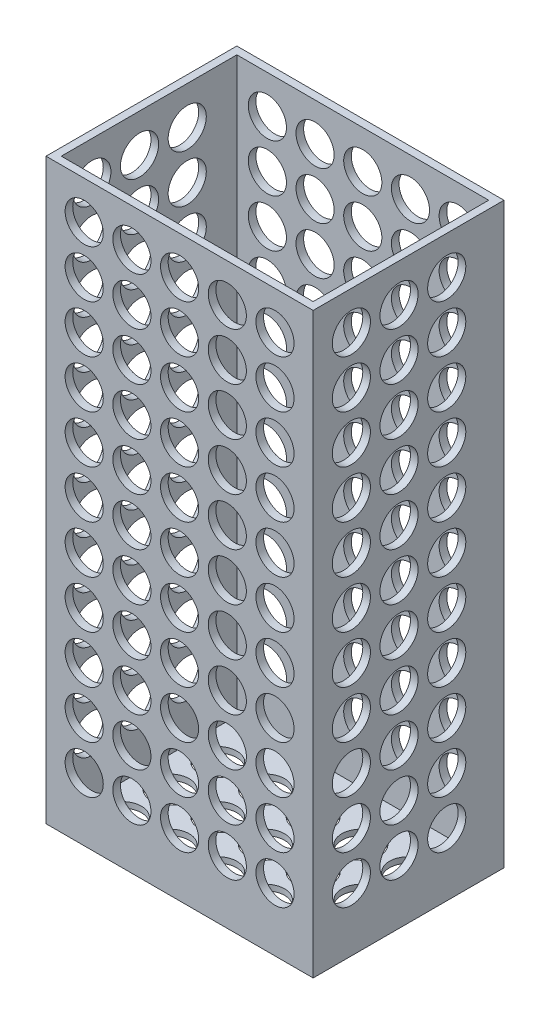
SolidWorks part; units mm, degrees
ref_plane "Front Plane" through (0, 0, 0) normal (0, 0, 1) x (1, 0, 0)
ref_plane "Top Plane" through (0, 0, 0) normal (0, 1, 0) x (1, 0, 0)
ref_plane "Right Plane" through (0, 0, 0) normal (1, 0, 0) x (0, 0, -1)
sketch "Sketch1" plane through (0, 0, 0) normal (0, 1, 0) x (1, 0, 0)
  line L1 (-35, -25) -> (35, -25)
  line L2 (-35, -25) -> (-35, 25)
  line L3 (-35, 25) -> (35, 25)
  line L4 (35, -25) -> (35, 25)
  line L5 (-35, -25) -> (35, 25) construction
  line L6 (-35, 25) -> (35, -25) construction
  point P0 (0, 0)
  dimension "D1" = 50
  dimension "D2" = 70
extrude "Boss-Extrude1" add sketch "Sketch1" along normal blind 1.5
sketch "Sketch2" plane through (0, 1.5, 0) normal (0, 1, 0) x (1, 0, 0)
  line L0 (-33, 23) -> (-33, -23)
  line L1 (-33, -23) -> (33, -23)
  line L2 (33, -23) -> (33, 23)
  line L3 (33, 23) -> (-33, 23)
  line L4 (35, -25) -> (35, 25)
  line L5 (35, 25) -> (-35, 25)
  line L6 (-35, 25) -> (-35, -25)
  line L7 (-35, -25) -> (35, -25)
  line L8 (35, -25) -> (35, 25)
  line L9 (35, 25) -> (-35, 25)
  line L10 (-35, 25) -> (-35, -25)
  line L11 (-35, -25) -> (35, -25)
  dimension "D1" = 0
  dimension "D2" = 2
extrude "Boss-Extrude2" add sketch "Sketch2" along normal blind 150
sketch "Sketch4" plane through (0, 0, 25) normal (0, 0, 1) x (1, 0, 0)
  line L0 (-35, 151.5) -> (35, 151.5) construction
  line L1 (-35, 151.5) -> (-35, 0) construction
  circle A0 centre (-25, 141.5) radius 5
  circle A1 centre (-12.5, 141.5) radius 5
  circle A2 centre (0, 141.5) radius 5
  circle A3 centre (12.5, 141.5) radius 5
  circle A4 centre (25, 141.5) radius 5
  circle A5 centre (-12.5, 129) radius 5
  circle A6 centre (0, 129) radius 5
  circle A7 centre (12.5, 129) radius 5
  circle A8 centre (25, 129) radius 5
  circle A9 centre (-12.5, 116.5) radius 5
  circle A10 centre (0, 116.5) radius 5
  circle A11 centre (12.5, 116.5) radius 5
  circle A12 centre (25, 116.5) radius 5
  circle A13 centre (-12.5, 104) radius 5
  circle A14 centre (0, 104) radius 5
  circle A15 centre (12.5, 104) radius 5
  circle A16 centre (25, 104) radius 5
  circle A17 centre (-12.5, 91.5) radius 5
  circle A18 centre (0, 91.5) radius 5
  circle A19 centre (12.5, 91.5) radius 5
  circle A20 centre (25, 91.5) radius 5
  circle A21 centre (-12.5, 79) radius 5
  circle A22 centre (0, 79) radius 5
  circle A23 centre (12.5, 79) radius 5
  circle A24 centre (25, 79) radius 5
  circle A25 centre (-12.5, 66.5) radius 5
  circle A26 centre (0, 66.5) radius 5
  circle A27 centre (12.5, 66.5) radius 5
  circle A28 centre (25, 66.5) radius 5
  circle A29 centre (-12.5, 54) radius 5
  circle A30 centre (0, 54) radius 5
  circle A31 centre (12.5, 54) radius 5
  circle A32 centre (25, 54) radius 5
  circle A33 centre (-12.5, 41.5) radius 5
  circle A34 centre (0, 41.5) radius 5
  circle A35 centre (12.5, 41.5) radius 5
  circle A36 centre (25, 41.5) radius 5
  circle A37 centre (-12.5, 29) radius 5
  circle A38 centre (0, 29) radius 5
  circle A39 centre (12.5, 29) radius 5
  circle A40 centre (25, 29) radius 5
  circle A41 centre (-12.5, 16.5) radius 5
  circle A42 centre (0, 16.5) radius 5
  circle A43 centre (12.5, 16.5) radius 5
  circle A44 centre (25, 16.5) radius 5
  circle A45 centre (-25, 129) radius 5
  circle A46 centre (-25, 116.5) radius 5
  circle A47 centre (-25, 104) radius 5
  circle A48 centre (-25, 91.5) radius 5
  circle A49 centre (-25, 79) radius 5
  circle A50 centre (-25, 66.5) radius 5
  circle A51 centre (-25, 54) radius 5
  circle A52 centre (-25, 41.5) radius 5
  circle A53 centre (-25, 29) radius 5
  circle A54 centre (-25, 16.5) radius 5
  dimension "D1" = 10
  dimension "D2" = 10
  dimension "D3" = 10
  dimension "D4" = 5
  dimension "D5" = 11
extrude "Cut-Extrude2" cut sketch "Sketch4" against normal blind 150
sketch "Sketch5" plane through (35, 0, 0) normal (1, 0, 0) x (0, 0, -1)
  line L0 (-25, 151.5) -> (25, 151.5) construction
  line L1 (-25, 151.5) -> (-25, 0) construction
  circle A0 centre (-15, 141.5) radius 5
  circle A1 centre (-2.5, 141.5) radius 5
  circle A2 centre (10, 141.5) radius 5
  circle A3 centre (-2.5, 129) radius 5
  circle A4 centre (10, 129) radius 5
  circle A5 centre (-2.5, 116.5) radius 5
  circle A6 centre (10, 116.5) radius 5
  circle A7 centre (-2.5, 104) radius 5
  circle A8 centre (10, 104) radius 5
  circle A9 centre (-2.5, 91.5) radius 5
  circle A10 centre (10, 91.5) radius 5
  circle A11 centre (-2.5, 79) radius 5
  circle A12 centre (10, 79) radius 5
  circle A13 centre (-2.5, 66.5) radius 5
  circle A14 centre (10, 66.5) radius 5
  circle A15 centre (-2.5, 54) radius 5
  circle A16 centre (10, 54) radius 5
  circle A17 centre (-2.5, 41.5) radius 5
  circle A18 centre (10, 41.5) radius 5
  circle A19 centre (-2.5, 29) radius 5
  circle A20 centre (10, 29) radius 5
  circle A21 centre (-2.5, 16.5) radius 5
  circle A22 centre (10, 16.5) radius 5
  circle A23 centre (-15, 129) radius 5
  circle A24 centre (-15, 116.5) radius 5
  circle A25 centre (-15, 104) radius 5
  circle A26 centre (-15, 91.5) radius 5
  circle A27 centre (-15, 79) radius 5
  circle A28 centre (-15, 66.5) radius 5
  circle A29 centre (-15, 54) radius 5
  circle A30 centre (-15, 41.5) radius 5
  circle A31 centre (-15, 29) radius 5
  circle A32 centre (-15, 16.5) radius 5
  dimension "D1" = 10
  dimension "D2" = 10
  dimension "D3" = 10
  dimension "D4" = 3
  dimension "D5" = 11
extrude "Cut-Extrude3" cut sketch "Sketch5" against normal blind 150
sketch "Sketch6" plane through (0, 0, 0) normal (0, -1, 0) x (1, 0, 0)
  line L0 (35, 25) -> (35, -25) construction
  line L1 (-35, 25) -> (35, 25) construction
  circle A0 centre (25, 15) radius 5
  circle A1 centre (12.5, 15) radius 5
  circle A2 centre (0, 15) radius 5
  circle A3 centre (-12.5, 15) radius 5
  circle A4 centre (-25, 15) radius 5
  circle A5 centre (12.5, 2.5) radius 5
  circle A6 centre (0, 2.5) radius 5
  circle A7 centre (-12.5, 2.5) radius 5
  circle A8 centre (-25, 2.5) radius 5
  circle A9 centre (12.5, -10) radius 5
  circle A10 centre (0, -10) radius 5
  circle A11 centre (-12.5, -10) radius 5
  circle A12 centre (-25, -10) radius 5
  circle A13 centre (25, 2.5) radius 5
  circle A14 centre (25, -10) radius 5
  dimension "D1" = 10
  dimension "D2" = 10
  dimension "D3" = 10
  dimension "D4" = 5
  dimension "D5" = 3
extrude "Cut-Extrude4" cut sketch "Sketch6" against normal blind 150
